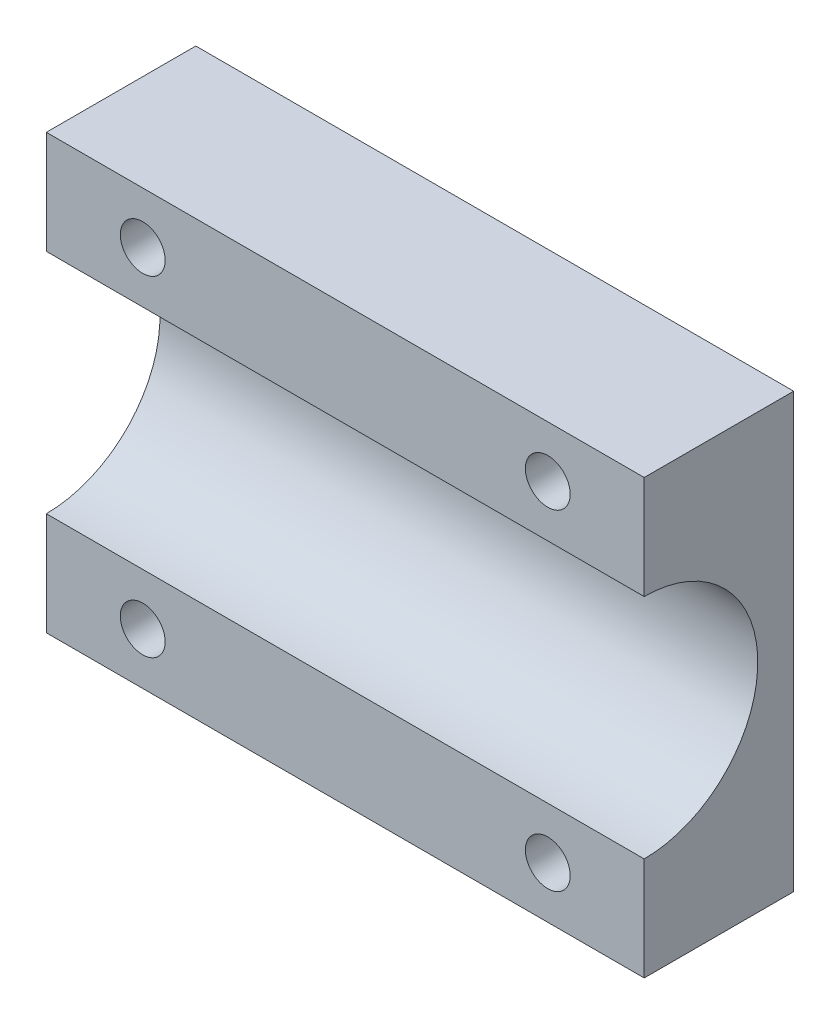
SolidWorks part; units mm, degrees
ref_plane "Front Plane" through (0, 0, 0) normal (1, 0, 0) x (0, 1, 0)
ref_plane "Top Plane" through (0, 0, 0) normal (0, 0, 1) x (0, 1, 0)
ref_plane "Right Plane" through (0, 0, 0) normal (0, 1, 0) x (-1, 0, 0)
sketch "Sketch1" plane through (0, 0, 0) normal (0, 0, 1) x (0, 1, 0)
  line L1 (0, 0) -> (29, 0)
  line L2 (0, 0) -> (0, -40)
  line L3 (0, -40) -> (29, -40)
  line L4 (29, 0) -> (29, -40)
  dimension "D1" = 29
  dimension "D2" = 40
extrude "Boss-Extrude1" add sketch "Sketch1" along normal blind 10 contours L4 L1 L2 L3
sketch "Sketch2" plane through (40, 0, 0) normal (1, 0, 0) x (0, 1, 0)
  line L0 (0, 10) -> (29, 10) construction
  circle A0 centre (14.5, 10) radius 7.6
  dimension "D1" = 15.2
extrude "Cut-Extrude1" cut sketch "Sketch2" against normal up to surface (40 mm away) up to face at (0, 14.5, 5)
sketch "Sketch3" plane through (0, 0, 10) normal (0, 0, 1) x (1, 0, 0)
  line L0 (0, 29) -> (12.9, 22.1) construction
  line L1 (40, 22.1) -> (0, 22.1) construction
  line L2 (0, 22.1) -> (12.9, 29) construction
  line L3 (0, 29) -> (40, 29) construction
  line L4 (40, 29) -> (27.1, 22.1) construction
  line L5 (40, 22.1) -> (27.1, 29) construction
  line L6 (0, 6.9) -> (12.9, 0) construction
  line L7 (0, 0) -> (40, 0) construction
  line L8 (0, 0) -> (12.9, 6.9) construction
  line L9 (0, 6.9) -> (40, 6.9) construction
  line L10 (40, 0) -> (27.1, 6.9) construction
  line L11 (40, 6.9) -> (27.1, 0) construction
  circle A0 centre (6.45, 25.55) radius 1.5
  circle A1 centre (33.55, 25.55) radius 1.5
  circle A2 centre (33.55, 3.45) radius 1.5
  circle A3 centre (6.45, 3.45) radius 1.5
  point P40 (0, 0)
  dimension "D1" = 3
  dimension "D2" = 12.9
  dimension "D3" = 12.9
extrude "Cut-Extrude2" cut sketch "Sketch3" against normal up to surface (10 mm away) up to face at (20, 14.5, 0)
equation "\"screw_hole\"= 3mm"
equation "\"offset\"= 2.52mm"
equation "\"y_length\" = 40mm"
equation "\"z_breadth\"= 29mm"
equation "\"D1@Sketch1\"=\"z_breadth\""
equation "\"D2@Sketch1\"=\"y_length\""
equation "\"lm8uu_bearing_dia\"= 15.2mm"
equation "\"D1@Sketch2\"=\"lm8uu_bearing_dia\""
equation "\"D1@Sketch3\"=\"screw_hole\""
equation "\"D3@Sketch3\"=\"D2@Sketch3\""
